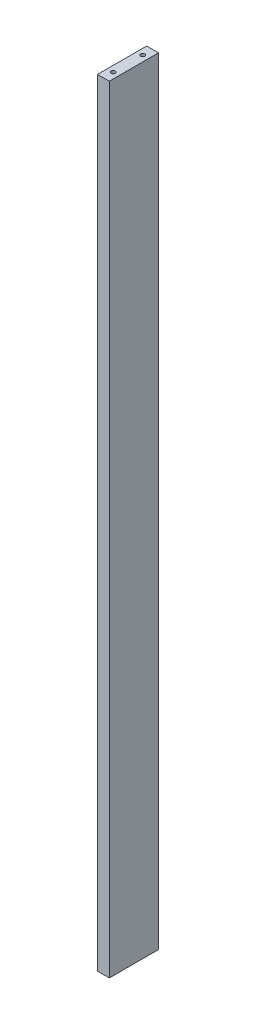
SolidWorks part; units mm, degrees
material "Beech"
ref_plane "Front Plane" through (0, 0, 0) normal (0, 0, 1) x (1, 0, 0)
ref_plane "Top Plane" through (0, 0, 0) normal (0, 1, 0) x (1, 0, 0)
ref_plane "Right Plane" through (0, 0, 0) normal (1, 0, 0) x (0, 0, -1)
sketch "Sketch1" plane through (0, 0, 0) normal (0, 1, 0) x (1, 0, 0)
  line L1 (0, 0) -> (12, 0)
  line L2 (0, 0) -> (0, 50)
  line L3 (0, 50) -> (12, 50)
  line L4 (12, 0) -> (12, 50)
  dimension "D1" = 12
  dimension "D2" = 50
extrude "base" add sketch "Sketch1" along normal blind 789.8
hole_wizard "end bolt holes for inserts" positions "Sketch2" profile "Sketch3" tap size "M5x0.8" standard "ANSI Metric"
sketch "Sketch2" plane through (0, 0, 0) normal (0, -1, 0) x (-1, 0, 0)
  line L1 (-6, 50) -> (-6, 0)
  line L2 (-12, 50) -> (0, 50) construction
  line L3 (0, 0) -> (-12, 0) construction
  line L4 (-6, 10) -> (-12, 25)
  line L5 (-12, 0) -> (-12, 50) construction
  line L6 (-12, 25) -> (-6, 40)
  point P10 (-6, 40)
  point P12 (-6, 10)
  dimension "D1" = 30
sketch "Sketch3" plane through (6, 0, -40) normal (1, 0, 0) x (0, 0, -1)
  line L0 (0, 0) -> (0, 15.2618)
  line L1 (0, 15.2618) -> (2.1, 14)
  line L2 (2.1, 14) -> (2.1, 0)
  line L5 (2.1, 0) -> (0, 0)
  line L10 (0, 15.2618) -> (-2.1, 14) construction
  line L11 (0, -6.35) -> (0, 107.95) construction
  dimension "Tap Drill Dia." = 4.2
  dimension "Tap Drill Depth" = 14
  dimension "Drill Angle" = 118
cosmetic thread "Hole Thread1" parameters "D1"=10, "D2"=5
cosmetic thread "Hole Thread2" parameters "D1"=10, "D2"=5
ref_plane "midplane along length" through (0, 394.9, 0) normal (0, -1, 0) x (-1, 0, 0)
mirror "mirror end bolt holes" about plane through (0, 394.9, 0) normal (0, -1, 0) of "end bolt holes for inserts"
equation "\"board_thickness\" = 12mm"
equation "\"way_width\"= 75mm"
equation "\"way_thickness\"= 50mm"
equation "\"radial_clearance\"= 0.1mm"
equation "\"slider_width\"= \"way_width\"-2* \"radial_clearance\""
equation "\"slider_thickness\" = \"way_thickness\" - 2 * \"radial_clearance\""
equation "\"column_width\"= \"way_width\" + 2 * \"board_thickness\""
equation "\"boxway_slot_width\" = 50mm"
equation "\"keeper_rail_width\" = (\"column_width\" - \"boxway_slot_width\")/2"
equation "\"slider_length\" = 125mm"
equation "\"nut_diameter\"= 22mm"
equation "\"nut_length\"= 15mm"
equation "\"leadscrew_diameter\"= 10mm"
equation "\"leadscrew_radial_clearance\"= 1mm"
equation "\"bearing_bolt_pattern_width\" = 35mm"
equation "\"bearing_bolt_pattern_height\" = 60mm"
equation "\"desktop_bolt_pattern_width\" = 30mm"
equation "\"desktop_bolt_pattern_height\" = 30mm"
equation "\"bearing_bolt_nut_counterbore_diameter\" = 12mm"
equation "\"bearing_bolt_nut_counterbore_depth\"= 10mm"
equation "\"desktop_depth\"= 500mm"
equation "\"desktop_width\"= 650mm"
equation "\"desktop_thickness\"= 15mm"
equation "\"leg_height\"=75mm"
equation "\"leg_width\"=12mm"
equation "\"leg_length\"=500mm"
equation "\"lap_joint_height\" = 50mm"
equation "\"lap_dowel_diameter\"= 8mm"
equation "\"lap_dowel_hole_z_spacing\"=30"
equation "\"D1@Sketch1\"=\"board_thickness\""
equation "\"D2@Sketch1\"=\"lap_joint_height\""
equation "\"D1@Sketch2\"=\"lap_dowel_hole_z_spacing\""
